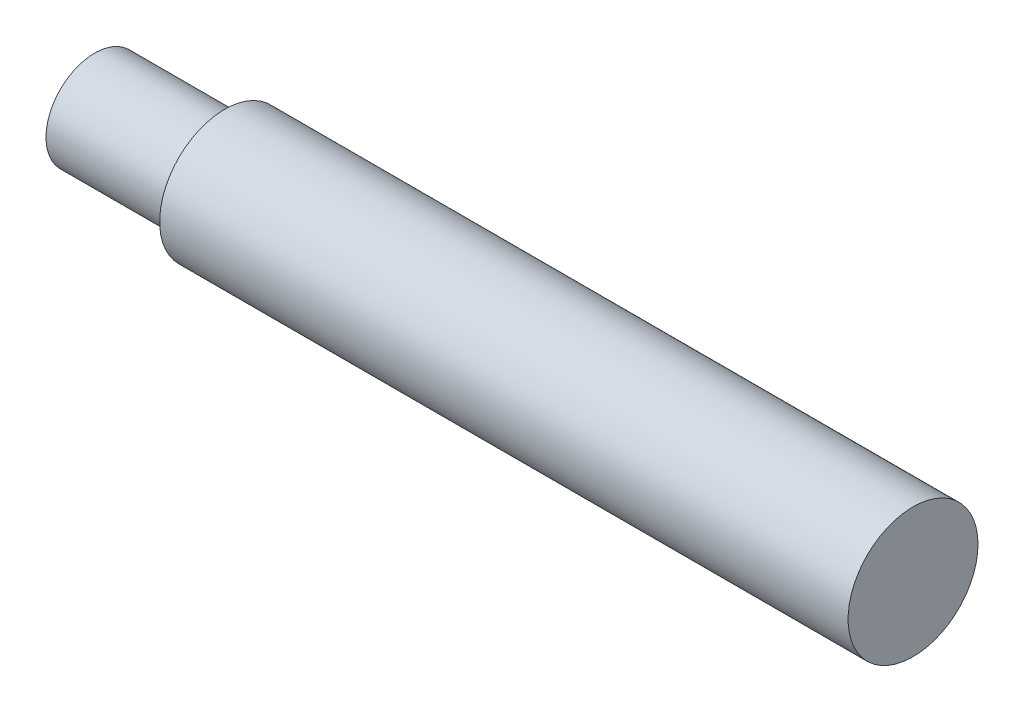
SolidWorks part; units mm, degrees
ref_plane "Alzado" through (0, 0, 0) normal (0, 0, 1) x (1, 0, 0)
ref_plane "Planta" through (0, 0, 0) normal (0, 1, 0) x (1, 0, 0)
ref_plane "Vista lateral" through (0, 0, 0) normal (1, 0, 0) x (0, 0, -1)
sketch "Sketch2" plane through (0, 0, 0) normal (1, 0, 0) x (0, 0, -1)
  circle A0 centre (0, 0) radius 10
extrude "Boss-Extrude1" add sketch "Sketch2" along normal blind 106 contours A0
sketch "Sketch3" plane through (0, 0, 0) normal (-1, 0, 0) x (0, 0, 1)
  circle A0 centre (0, 0) radius 7.5
extrude "Boss-Extrude2" add sketch "Sketch3" along normal blind 20
